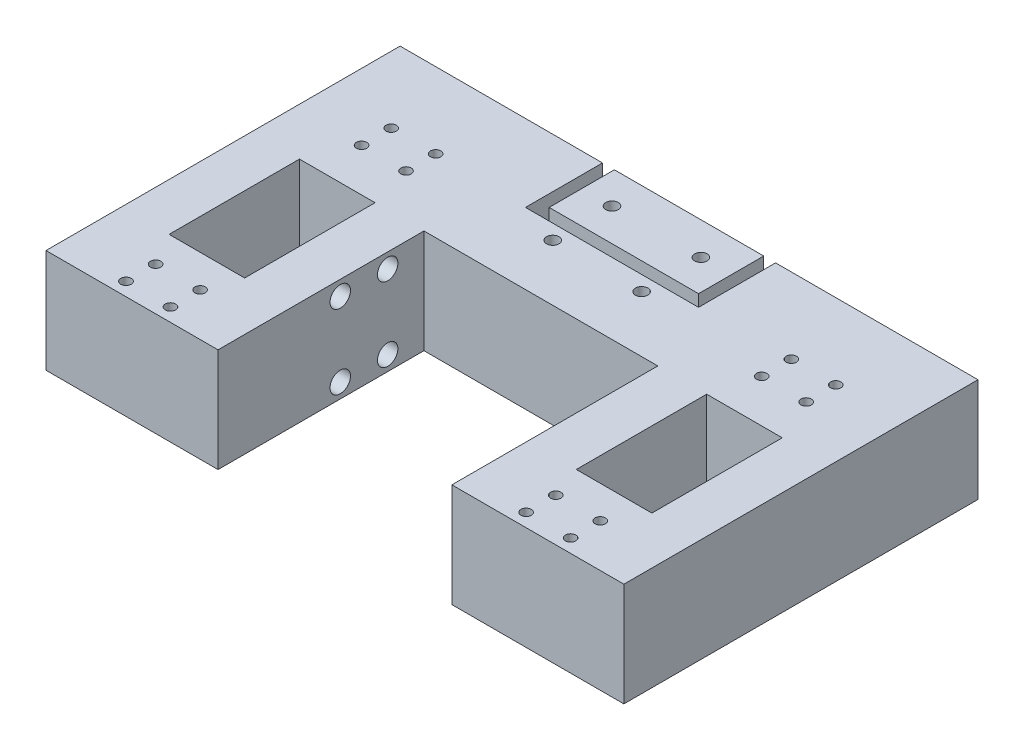
SolidWorks part; units mm, degrees
ref_plane "前视基准面" through (0, 0, 0) normal (0, 0, 1) x (1, 0, 0)
ref_plane "上视基准面" through (0, 0, 0) normal (0, 1, 0) x (1, 0, 0)
ref_plane "右视基准面" through (0, 0, 0) normal (1, 0, 0) x (0, 0, -1)
sketch "Sketch1" plane through (0, 0, 0) normal (0, 1, 0) x (1, 0, 0)
  line L1 (-97.5, 25) -> (97.5, 25)
  line L2 (-97.5, 25) -> (-97.5, -25)
  line L3 (-97.5, -25) -> (97.5, -25)
  line L4 (97.5, 25) -> (97.5, -25)
  line L5 (0, -25) -> (0, 25) construction
  line L6 (-97.5, 0) -> (97.5, 0) construction
  point P0 (0, 0)
  dimension "D1" = 195
  dimension "D2" = 50
extrude "Boss-Extrude1" add sketch "Sketch1" along normal blind 35
sketch "Sketch2" plane through (0, 35, 0) normal (0, 1, 0) x (1, 0, 0)
  line L0 (97.5, 25) -> (-97.5, 25) construction
  line L1 (-32.5, -15) -> (32.5, -15)
  line L2 (-32.5, -15) -> (-32.5, 25)
  line L3 (-32.5, 25) -> (32.5, 25)
  line L4 (32.5, -15) -> (32.5, 25)
  line L5 (0, 25) -> (0, -15) construction
  line L6 (-32.5, 5) -> (32.5, 5) construction
  point P0 (0, 5)
  dimension "D1" = 40
  dimension "D2" = 65
sketch "Sketch5" plane through (0, 35, 0) normal (0, 1, 0) x (1, 0, 0)
  line L0 (-15, 14) -> (15, 14) construction
  line L1 (-15, 14) -> (-15, -6) construction
  line L2 (97.5, 25) -> (-97.5, 25) construction
  circle A0 centre (15, 14) radius 2.1
  circle A1 centre (-15, 14) radius 2.1
  circle A2 centre (-15, -6) radius 2.1
  circle A3 centre (15, -6) radius 2.1
  point P3 (0, 14)
  dimension "D1" = 4.2
  dimension "D2" = 30
  dimension "D3" = 20
  dimension "D4" = 11
sketch "Sketch8" plane through (0, 0, 0) normal (0, 1, 0) x (1, 0, 0)
  line L0 (-97.5, -25) -> (97.5, -25) construction
  line L1 (55.9525, -25) -> (81.4525, -25)
  line L2 (55.9525, -25) -> (55.9525, -69)
  line L3 (55.9525, -69) -> (81.4525, -69)
  line L4 (81.4525, -25) -> (81.4525, -69)
  line L5 (97.5, -25) -> (97.5, 25) construction
  line L6 (39.4525, -25) -> (97.5, -25)
  line L7 (39.4525, -25) -> (39.4525, -94.4868)
  line L8 (39.4525, -94.4868) -> (97.5, -94.4868)
  line L9 (97.5, -25) -> (97.5, -94.4868)
  line L10 (97.5, -25) -> (97.5, 25) construction
  dimension "D1" = 25.5
  dimension "D2" = 44
  dimension "D3" = 16.5
  dimension "D4" = 16.0475
extrude "Boss-Extrude4" add sketch "Sketch8" along normal up to surface (35 mm away) contours L9 L6 L4 L3 L2 L7 L8 up to face at (0, 35, 0)
sketch "Sketch11" plane through (0, 0, 0) normal (0, 1, 0) x (1, 0, 0)
  circle A8 centre (75.0058, -0.5) radius 1.75
  circle A9 centre (60.0058, -0.5) radius 1.75
  circle A10 centre (60.0058, -10.5) radius 1.75
  circle A11 centre (75.0058, -10.5) radius 1.75
  circle A12 centre (75.0058, -79.9868) radius 1.75
  circle A13 centre (75.0058, -89.9868) radius 1.75
  circle A14 centre (60.0058, -79.9868) radius 1.75
  circle A15 centre (60.0058, -89.9868) radius 1.75
extrude "Cut-Extrude5" cut sketch "Sketch11" along normal up to next
mirror "Mirror2" about plane through (0, 0, 0) normal (1, 0, 0) of "Cut-Extrude5", "Boss-Extrude4"
sketch "Sketch12" plane through (39.4525, 0, 0) normal (-1, 0, 0) x (0, 0, 1)
  line L0 (25, 0) -> (94.4868, 0) construction
  line L1 (37.2434, 30) -> (53.2434, 30) construction
  line L2 (37.2434, 30) -> (37.2434, 5) construction
  line L3 (37.2434, 5) -> (53.2434, 5) construction
  line L4 (53.2434, 30) -> (53.2434, 5) construction
  line L5 (45.2434, 5) -> (45.2434, 30) construction
  line L6 (37.2434, 17.5) -> (53.2434, 17.5) construction
  line L9 (35.2434, 187.6354) -> (35.2434, -212.3646) construction
  line L10 (55.2434, 187.6354) -> (55.2434, -212.3646) construction
  circle A0 centre (53.2434, 30) radius 3.45
  circle A1 centre (37.2434, 30) radius 3.45
  circle A2 centre (53.2434, 5) radius 3.45
  circle A3 centre (37.2434, 5) radius 3.45
  point P0 (45.2434, 17.5)
  dimension "D3" = 6.9
  dimension "D1" = 16
  dimension "D2" = 25
  dimension "D4" = 17.5
  dimension "D5" = 10
extrude "Cut-Extrude6" cut sketch "Sketch5" against normal blind 6
sketch "Sketch15" plane through (0, 35, 0) normal (0, 1, 0) x (1, 0, 0)
  line L4 (0, 25) -> (0, -15) construction
  line L5 (-32.5, 25) -> (32.5, 25) construction
  line B0 (-29.2, -1) -> (29.2, -1)
  line B1 (-29.2, -1) -> (-29.2, 25)
  line B2 (-29.2, 25) -> (29.2, 25)
  line B3 (29.2, -1) -> (29.2, 25)
  line B4 (0, 25) -> (0, -1) construction
  line B5 (-29.2, 12) -> (29.2, 12) construction
  line B6 (-25.2, 3) -> (-25.2, 21)
  line B7 (25.2, 3) -> (25.2, 21)
  line B8 (-25.2, 3) -> (25.2, 3)
  line B9 (-25.2, 21) -> (-25.2, 25)
  line B10 (-25.2, 25) -> (25.2, 25)
  line B11 (25.2, 25) -> (25.2, 21)
  line M40 (97.5, 25) -> (-97.5, 25)
sketch_block_instance "Block2-1"
sketch_block "Block2"
extrude "Cut-Extrude7" cut sketch "Sketch15" against normal blind 27 contours B11 B7 B8 B6 B9 B2 B1 B0 B3 M40
extrude "Cut-Extrude8" cut sketch "Sketch12" against normal blind 12
mirror "Mirror3" about plane through (0, 0, 0) normal (1, 0, 0) of "Cut-Extrude8"
